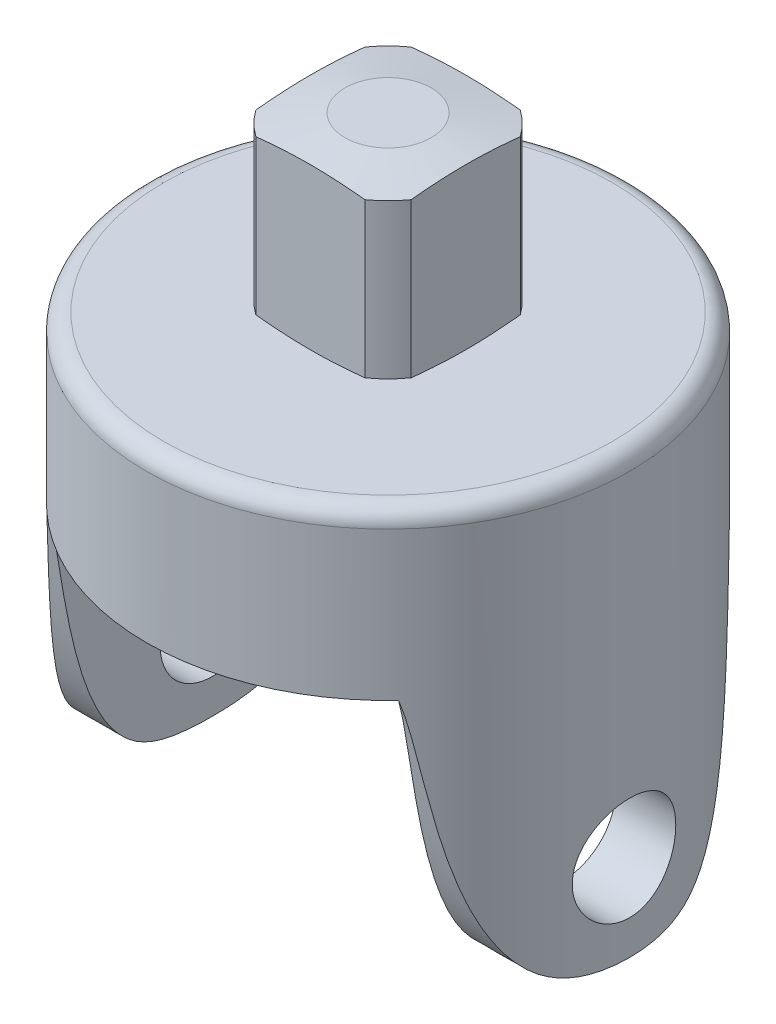
SolidWorks part; units mm, degrees
ref_plane "Front Plane" through (0, 0, 0) normal (0, 0, 1) x (1, 0, 0)
ref_plane "Top Plane" through (0, 0, 0) normal (0, 1, 0) x (1, 0, 0)
ref_plane "Right Plane" through (0, 0, 0) normal (1, 0, 0) x (0, 0, -1)
sketch "Sketch1" plane through (0, 0, 0) normal (0, 1, 0) x (1, 0, 0)
  circle A0 centre (0, 0) radius 70
  dimension "D1" = 140
extrude "Boss-Extrude1" add sketch "Sketch1" along normal blind 102 and the other way blind 30
sketch "Sketch2" plane through (0, 102, 0) normal (0, 1, 0) x (1, 0, 0)
  line L1 (-22.5, 22.5) -> (22.5, 22.5)
  line L2 (-22.5, 22.5) -> (-22.5, -22.5)
  line L3 (-22.5, -22.5) -> (22.5, -22.5)
  line L4 (22.5, 22.5) -> (22.5, -22.5)
  line L5 (-22.5, 22.5) -> (22.5, -22.5) construction
  line L6 (-22.5, -22.5) -> (22.5, 22.5) construction
  point P0 (0, 0)
  dimension "D1" = 45
extrude "Boss-Extrude2" add sketch "Sketch2" along normal blind 50
ref_axis "Axis1" through (0, 160.85, 0) along (0, -1, 0)
sketch "Sketch3" plane through (0, 0, 0) normal (0, 0, 1) x (1, 0, 0)
  line L0 (-12.5, 152) -> (-47.5128, 152)
  line L1 (-22.5, 152) -> (22.5, 152) construction
  line L2 (-47.5128, 152) -> (-47.5128, 102)
  line L3 (70, 102) -> (-70, 102) construction
  line L4 (-47.5128, 102) -> (-12.5, 102)
  line L5 (-22.5, 102) -> (22.5, 102) construction
  line L6 (-12.5, 102) -> (-27.5, 104.6449)
  line L8 (-27.5, 149.3551) -> (-12.5, 152)
  line L9 (-22.5, 152) -> (-22.5, 102) construction
  line L10 (-27.5, 149.3551) -> (-27.5, 104.6449)
  dimension "D1" = 10
  dimension "D2" = 10
  dimension "D4" = 10
  dimension "D5" = 15
fillet "Fillet1" radius 5 1 edges at (0, 102, 70)
fillet "Fillet2" radius 5 1 edges at (0, -30, 70)
revolve "Cut-Revolve2" cut sketch "Sketch3" angle 360 about axis through (0, 160.85, 0) along (0, -1, 0)
sketch "Sketch4" plane through (0, -30, 0) normal (0, -1, 0) x (1, 0, 0)
  line L1 (-51, 75) -> (51, 75)
  line L2 (-51, 75) -> (-51, -75)
  line L3 (-51, -75) -> (51, -75)
  line L4 (51, 75) -> (51, -75)
  line L5 (-51, 75) -> (51, -75) construction
  line L6 (-51, -75) -> (51, 75) construction
  point P0 (0, 0)
  dimension "D1" = 102
  dimension "D2" = 150
extrude "Cut-Extrude1" cut sketch "Sketch4" against normal blind 84 contours L3 L4 L1 L2
sketch "Sketch5" plane through (0, 0, 0) normal (1, 0, 0) x (0, 0, -1)
  line L0 (-47.9479, -25) -> (47.9479, -25) construction
  line L1 (0, 77) -> (0, -77) construction
  line L3 (-47.9479, 54) -> (-70, 54)
  line L4 (-70, 54) -> (-70, -34.2104)
  line L5 (-70, -34.2104) -> (78.0249, -34.2104)
  line L6 (78.0249, -34.2104) -> (78.0249, 54)
  line L7 (78.0249, 54) -> (47.9479, 54)
  spline S0 degree 3 poles (47.9479, 54) (43.1741, 36.1139) (41.3075, -20.2236) (8.9796, -25) (0, -25) knots 0 0 0 0 0.785107 1 1 1 1
  spline S1 degree 3 poles (-47.9479, 54) (-43.1741, 36.1139) (-41.3075, -20.2236) (-8.9796, -25) (0, -25) knots 0 0 0 0 0.785107 1 1 1 1
extrude "Cut-Extrude3" cut sketch "Sketch5" against normal mid plane 144 contours L5 L6 L7 S0 S1 L3 L4
sketch "Sketch6" plane through (0, 0, 0) normal (1, 0, 0) x (0, 0, -1)
  circle A0 centre (0, 0) radius 15
  dimension "D1" = 30
extrude "Cut-Extrude4" cut sketch "Sketch6" against normal through all both and the other way through all
